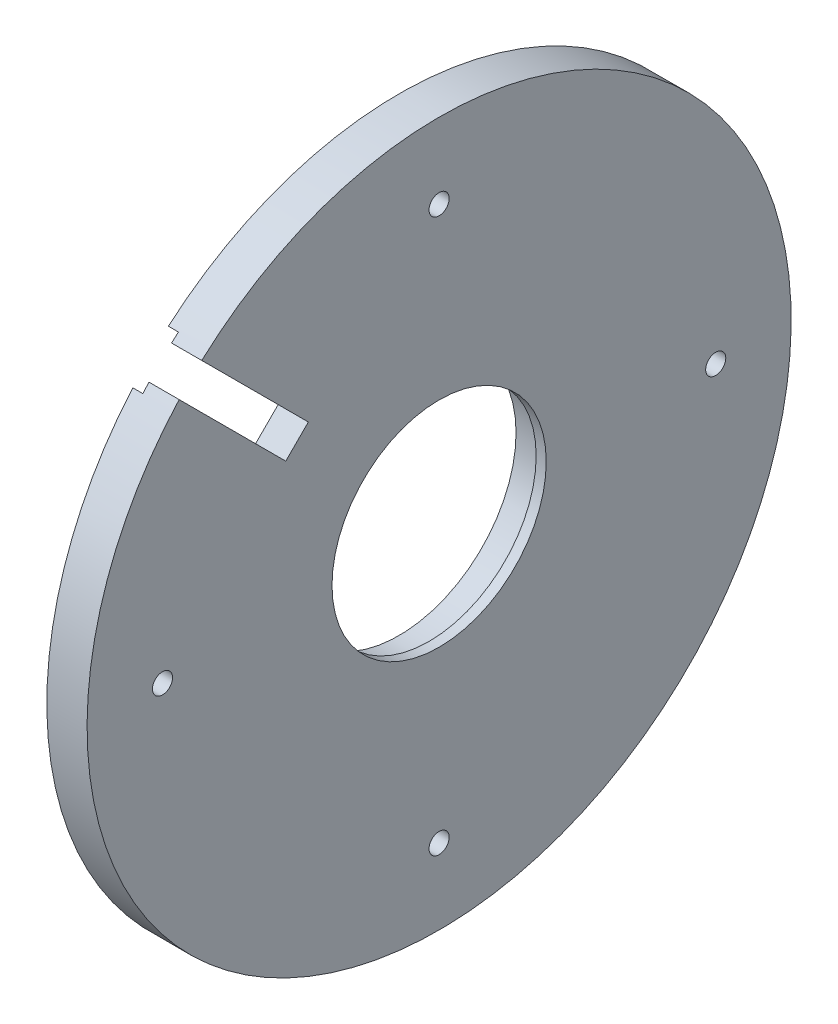
SolidWorks part; units mm, degrees
material "6061 Alloy"
ref_plane "Front Plane" through (0, 0, 0) normal (0, 0, 1) x (1, 0, 0)
ref_plane "Top Plane" through (0, 0, 0) normal (0, 1, 0) x (1, 0, 0)
ref_plane "Right Plane" through (0, 0, 0) normal (1, 0, 0) x (0, 0, -1)
sketch "Sketch1" plane through (0, 0, 0) normal (1, 0, 0) x (0, -0.1678, -0.9858)
  circle A0 centre (-28.5429, 18.9571) radius 11.65
  circle A1 centre (-28.5429, 18.9571) radius 35
  dimension "D1" = 70
extrude "Boss-Extrude1" add sketch "Sketch1" along normal blind 4
sketch "Sketch2" plane through (0, 0, 0) normal (-1, 0, 0) x (0, 0, 1)
  line L6 (38.3756, 38.3083) -> (48.9998, 48.9326)
  line L7 (50.4141, 47.5183) -> (54.0073, 51.1116)
  line L11 (54.0073, 51.1116) -> (51.312, 52.9305)
  line L12 (51.312, 52.9305) -> (48.9998, 48.9326)
  line L13 (39.7898, 36.8941) -> (50.4141, 47.5183)
  arc A2 (39.7898, 36.8941) -> (38.3756, 38.3083) centre (24.9582, 23.4767) ccw
extrude "Cut-Extrude1" cut sketch "Sketch2" against normal blind 10
sketch "Sketch6" plane through (4, 0, 0) normal (1, 0, 0) x (0, 0, -1)
  line L0 (-24.9582, 23.4767) -> (10.0418, 23.4767) construction
  arc A0 (-50.404, 47.5082) -> (-48.9897, 48.9225) centre (-24.9582, 23.4767) ccw construction
  circle A1 centre (-24.9582, -4.0233) radius 1
  circle A2 centre (2.5418, 23.4767) radius 1
  circle A3 centre (-52.4582, 23.4767) radius 1
  circle A4 centre (-24.9582, 50.9767) radius 1
  dimension "D1" = 4
extrude "Cut-Extrude4" cut sketch "Sketch6" against normal blind 10
sketch "Sketch7" plane through (4, 0, 0) normal (-1, 0, 0) x (0, 0, 1)
  circle A1 centre (24.9582, 23.4767) radius 11.65
  circle A2 centre (24.9582, 23.4767) radius 10.65
extrude "Boss-Extrude3" add sketch "Sketch7" along normal blind 1
sketch "Sketch8" plane through (3, 0, 0) normal (-1, 0, 0) x (0, 0, 1)
  circle A0 centre (24.9582, 23.4767) radius 11.65
  circle A1 centre (24.9582, 23.4767) radius 11.15
  dimension "D1" = 0.5
extrude "Cut-Extrude5" cut sketch "Sketch8" against normal blind 0.25
fillet "Fillet1" radius 0.1 1 edges at (3.25, 23.4767, 36.1082)
sketch "Sketch9" plane through (0, 0, 0) normal (-1, 0, 0) x (0, 0, 1)
  line L0 (48.9897, 48.9225) -> (50.404, 47.5082)
  line L1 (50.404, 47.5082) -> (40.4029, 37.5072)
  line L3 (38.9887, 38.9215) -> (48.9897, 48.9225)
  line L4 (36.2542, 38.3083) -> (48.9897, 51.0438)
  line L5 (48.9897, 51.0438) -> (52.5253, 47.5082)
  line L6 (52.5253, 47.5082) -> (39.7898, 34.7727)
  line L7 (36.2542, 38.3083) -> (35.5471, 37.6012)
  line L8 (39.7898, 34.7727) -> (36.2542, 38.3083) construction
  line L9 (35.5471, 37.6012) -> (39.0827, 34.0656)
  line L10 (39.7898, 34.7727) -> (39.0827, 34.0656)
  line L11 (38.9887, 38.9215) -> (40.4029, 37.5072)
  line L12 (38.3756, 38.3083) -> (48.9897, 48.9225) construction
  line L13 (39.7898, 36.8941) -> (38.3756, 38.3083) construction
  line L14 (50.404, 47.5082) -> (39.7898, 36.8941) construction
  dimension "D2" = 1
  dimension "D1" = 1.5
extrude "Cut-Extrude6" cut sketch "Sketch9" against normal blind 1
extrude "Cut-Extrude12" cut sketch "Sketch15" against normal blind 6
sketch "Sketch15" plane through (4, 2.2652, 47.8257) normal (1, 0, 0) x (0, 0, -1)
  line L2 (7.62, 34.2129) -> (9.8656, 36.4585)
  line L3 (9.8479, 36.4761) -> (-10.674, 56.998)
  line L4 (9.8479, 36.4761) -> (9.8656, 36.4585)
  line L5 (7.6028, 34.2311) -> (-12.919, 54.753)
  line L6 (-10.674, 56.998) -> (-12.919, 54.753)
  line L8 (7.62, 34.2129) -> (7.6028, 34.2311)
